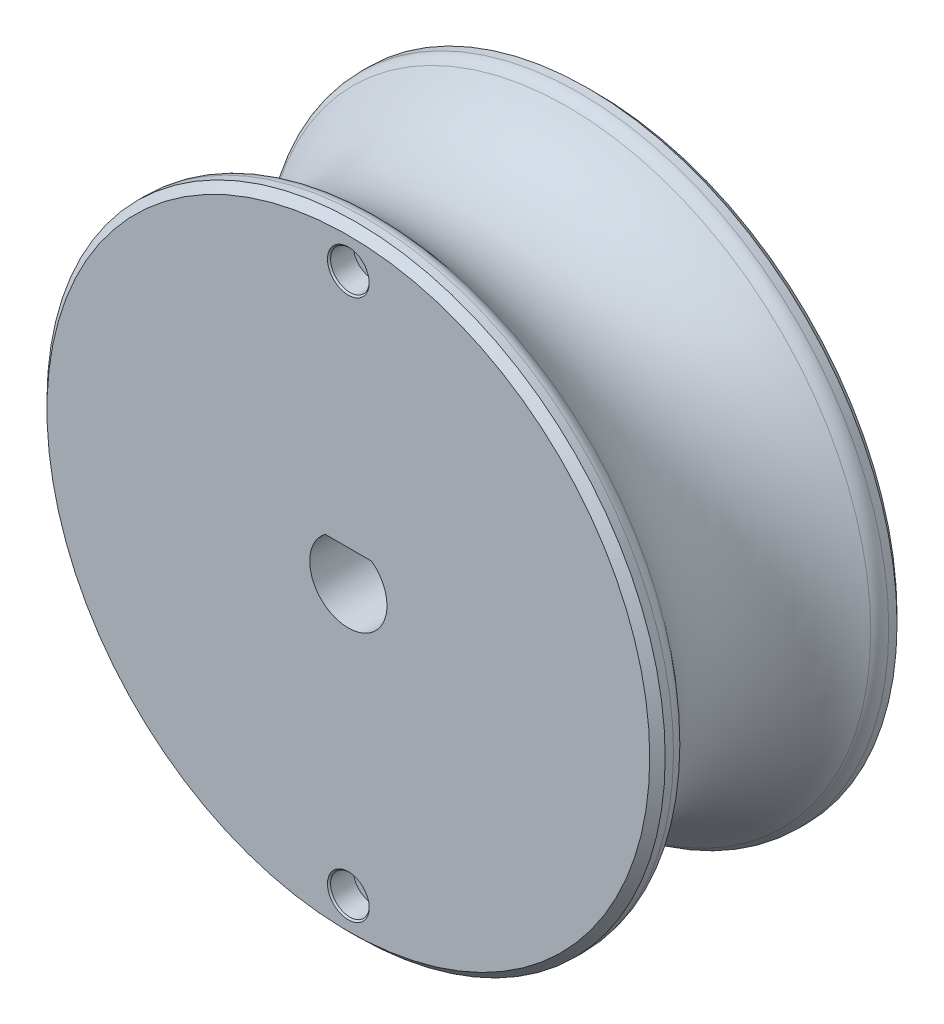
SolidWorks part; units mm, degrees
ref_plane "Front Plane" through (0, 0, 0) normal (0, 0, 1) x (1, 0, 0)
ref_plane "Top Plane" through (0, 0, 0) normal (0, 1, 0) x (1, 0, 0)
ref_plane "Right Plane" through (0, 0, 0) normal (1, 0, 0) x (0, 0, -1)
sketch "Sketch1" plane through (0, 0, 0) normal (0, 0, 1) x (1, 0, 0)
  circle A0 centre (0, 0) radius 50.8
  dimension "D1" = 101.6
extrude "Boss-Extrude1" add sketch "Sketch1" along normal mid plane 40.64
sketch "Sketch2" plane through (0, 0, 20.32) normal (0, 0, 1) x (1, 0, 0)
  line L0 (-1.6583, 2.5) -> (1.6583, 2.5)
  line L1 (22.352, 0) -> (-22.352, 0) construction
  arc A0 (-1.6583, 2.5) -> (1.6583, 2.5) centre (0, 0) ccw
  dimension "D1" = 3
  dimension "D2" = 2.5
extrude "Cut-Extrude1" cut sketch "Sketch2" against normal blind 14
sketch "Sketch3" plane through (0, 0, 20.32) normal (0, 0, 1) x (1, 0, 0)
  circle A0 centre (-1.6583, 2.5) radius 1.27
  circle A1 centre (1.6583, 2.5) radius 1.27
  dimension "D1" = 2.54
extrude "Cut-Extrude2" cut sketch "Sketch3" against normal blind 14
ref_axis "Axis1" through (0, 0, 6.32) along (0, 0, 1)
sketch "Sketch4" plane through (0, 0, 0) normal (1, 0, 0) x (0, 0, -1)
  line L0 (20.32, 50.8) -> (-20.32, 50.8) construction
  line L1 (0, 55.88) -> (0, -55.88) construction
  circle A0 centre (0, 62.23) radius 20
  dimension "D1" = 40
  dimension "D2" = 11.43
revolve "Cut-Revolve1" cut sketch "Sketch4" angle 360 about axis through (0, 0, 6.32) along (0, 0, 1)
fillet "Fillet2" radius 2.54 2 edges at (-50.8, 0, 16.412) (50.8, 0, -16.412)
chamfer "Chamfer1" distance 1.27 angle 45 5 edges at (-2.1523, 3.67, 20.32) (2.1523, 3.67, 20.32) (0, -3, 20.32) (50.8, 0, -20.32) (50.8, 0, 20.32)
sketch "Sketch5" plane through (0, 0, 20.32) normal (0, 0, 1) x (1, 0, 0)
  line L0 (0, -22.352) -> (0, 22.352) construction
  line L1 (22.352, 0) -> (-22.352, 0) construction
  circle A0 centre (0, -44.45) radius 3.175
  dimension "D1" = 6.35
  dimension "D2" = 44.45
extrude "Cut-Extrude3" cut sketch "Sketch5" against normal blind 4
mirror "Mirror1" about plane through (0, 0, 0) normal (0, 1, 0) of "Cut-Extrude3"
chamfer "Chamfer2" distance 0.254 angle 45 2 edges at (3.175, -44.45, 20.32) (3.175, 44.45, 20.32)
sketch "Sketch7" plane through (0, 0, -20.32) normal (0, 0, -1) x (-1, 0, 0)
  circle A0 centre (0, 0) radius 3.95
  dimension "D1" = 7.9
extrude "Boss-Extrude2" add sketch "Sketch7" along normal blind 8.89
sketch "Sketch8" plane through (0, 0, -20.32) normal (0, 0, -1) x (-1, 0, 0)
  circle A0 centre (0, 0) radius 4.7625
  dimension "D1" = 9.525
extrude "Boss-Extrude3" add sketch "Sketch8" along normal offset from surface (0.89 mm away) 8
chamfer "Chamfer3" distance 0.254 angle 45 2 edges at (4.7625, 0, -20.32) (-3.95, 0, -29.21)
mirror "Mirror2" about plane through (0, 0, 0) normal (0, 0, 1) of "Mirror1", "Cut-Extrude3"
sketch "Sketch10" plane through (0, 0, 20.32) normal (0, 0, 1) x (1, 0, 0)
  line L0 (-3.81, 5.08) -> (3.81, 5.08)
  line L1 (22.4536, 0) -> (-22.4536, 0) construction
  arc A0 (-3.81, 5.08) -> (3.81, 5.08) centre (0, 0) ccw
  point P1 (6.4587, 8.1327)
  dimension "D1" = 6.35
  dimension "D2" = 5.08
extrude "Cut-Extrude4" cut sketch "Sketch10" against normal up to surface and the other way through all
